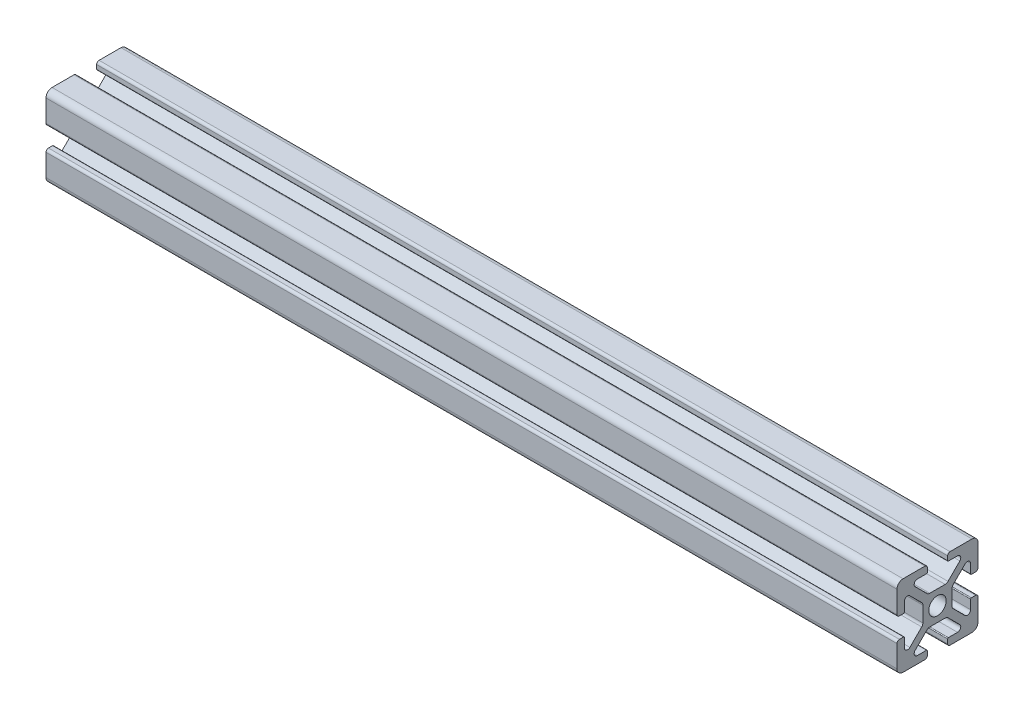
SolidWorks part; units mm, degrees
ref_plane "Front Plane" through (0, 0, 0) normal (0, 0, 1) x (1, 0, 0)
ref_plane "Top Plane" through (0, 0, 0) normal (0, 1, 0) x (1, 0, 0)
ref_plane "Right Plane" through (0, 0, 0) normal (1, 0, 0) x (0, 0, -1)
sketch "Sketch1" plane through (0, 0, 0) normal (1, 0, 0) x (0, 0, -1)
  line L0 (0, -10) -> (0, 10) construction
  line L1 (10, -10) -> (-10, -10)
  line L2 (10, -10) -> (10, 10)
  line L3 (10, 10) -> (0, 10)
  line L4 (-10, -10) -> (-10, 10)
  line L5 (10, -10) -> (-10, 10) construction
  line L6 (10, 10) -> (-10, -10) construction
  line L7 (10, 0) -> (-10, 0) construction
  line L8 (-2.5, 9.4) -> (-2.5, 8.3731)
  line L9 (-2.7, 8.1731) -> (-4.95, 8.1731)
  line L10 (-5.5157, 6.8075) -> (-2.6011, 3.8929)
  line L11 (-1.894, 3.6) -> (0, 3.6)
  line L12 (-5.3502, 4.0584) -> (-4.0584, 5.3502) construction
  line L13 (-3.825, 8.1731) -> (-3.825, 10) construction
  line L14 (-3.1, 10) -> (-10, 10)
  line L15 (-5.75, 7.3731) -> (5.75, 7.3731) construction
  circle A0 centre (0, 0) radius 2.15
  arc A1 (-4.95, 8.1731) -> (-5.5157, 6.8075) centre (-4.95, 7.3731) ccw
  arc A2 (-2.6011, 3.8929) -> (-1.894, 3.6) centre (-1.894, 4.6) ccw
  arc A3 (-2.5, 8.3731) -> (-2.7, 8.1731) centre (-2.7, 8.3731) cw
  arc A4 (-2.5, 9.4) -> (-3.1, 10) centre (-3.1, 9.4) ccw
  point P0 (0, 0)
  point P9 (0, 0)
  point P12 (0, 0)
  point P22 (-4.7043, 4.7043)
  point P32 (-2.5, 10)
  point P33 (-2.5, 8.8866)
  point P35 (-4.0584, 5.3502)
  point P37 (0, 7.3731)
  dimension "Center Hole Diameter" = 4.3
  dimension "D4" = 1
  dimension "D5" = 0.2
  dimension "D6" = 0.6
  dimension "D3" = 0.8
  dimension "Rail Height" = 20
  dimension "D7" = 6.4
  dimension "T Slot Width" = 5
  dimension "D10" = 10
  dimension "Rail Width" = 20
  dimension "D2" = 11.5
sketch "Sketch2" plane through (0, 0, 0) normal (0, 0, 1) x (1, 0, 0)
  line L0 (-132.4, 10) -> (-132.4, -10) construction
  line L1 (152.4, -10) -> (-152.4, -10) construction
  line L2 (152.4, -10) -> (152.4, 10) construction
  line L3 (152.4, 10) -> (-152.4, 10) construction
  line L4 (-152.4, -10) -> (-152.4, 10) construction
  line L5 (152.4, -10) -> (-152.4, 10) construction
  line L6 (152.4, 10) -> (-152.4, -10) construction
  line L7 (132.4, 10) -> (132.4, -10) construction
  point P0 (0, 0)
  point P12 (132.4, 0)
  dimension "Length" = 304.8
  dimension "D1" = 20
  dimension "D2" = 20
sketch "Sketch3" plane through (0, 0, 0) normal (1, 0, 0) x (0, 0, -1)
  line L0 (-5.5157, 6.8075) -> (-2.6011, 3.8929) construction
  line L5 (-3.1, 10) -> (-10, 10) construction
  line L6 (-2.5, 9.4) -> (-2.5, 8.3731) construction
  line L7 (-2.7, 8.1731) -> (-4.95, 8.1731) construction
  line L8 (-1.894, 3.6) -> (0, 3.6) construction
  line L9 (-5.5157, 6.8075) -> (-2.6011, 3.8929)
  line L10 (-10, 10) -> (0, 0) construction
  line L12 (-3.6, 1.894) -> (-3.6, 0)
  line L13 (-8.1731, 2.7) -> (-8.1731, 4.95)
  line L14 (-3.1, 10) -> (-8.5, 10)
  line L15 (-2.5, 9.4) -> (-2.5, 8.3731)
  line L16 (-2.7, 8.1731) -> (-4.95, 8.1731)
  line L17 (-1.894, 3.6) -> (0, 3.6)
  line L18 (-9.4, 2.5) -> (-8.3731, 2.5)
  line L19 (-10, 3.1) -> (-10, 8.5)
  line L20 (-6.8075, 5.5157) -> (-3.8929, 2.6011)
  line L21 (-3.6, 0) -> (-2.15, 0)
  line L22 (0, 3.6) -> (0, 2.15)
  arc A0 (-2.5, 9.4) -> (-3.1, 10) centre (-3.1, 9.4) ccw construction
  arc A1 (-2.7, 8.1731) -> (-2.5, 8.3731) centre (-2.7, 8.3731) ccw construction
  arc A2 (-4.95, 8.1731) -> (-5.5157, 6.8075) centre (-4.95, 7.3731) ccw construction
  arc A3 (-2.6011, 3.8929) -> (-1.894, 3.6) centre (-1.894, 4.6) ccw construction
  arc A4 (-2.5, 9.4) -> (-3.1, 10) centre (-3.1, 9.4) ccw
  arc A5 (-2.7, 8.1731) -> (-2.5, 8.3731) centre (-2.7, 8.3731) ccw
  arc A6 (-4.95, 8.1731) -> (-5.5157, 6.8075) centre (-4.95, 7.3731) ccw
  arc A7 (-2.6011, 3.8929) -> (-1.894, 3.6) centre (-1.894, 4.6) ccw
  arc A8 (-3.8929, 2.6011) -> (-3.6, 1.894) centre (-4.6, 1.894) cw
  arc A9 (-8.1731, 4.95) -> (-6.8075, 5.5157) centre (-7.3731, 4.95) cw
  arc A10 (-8.1731, 2.7) -> (-8.3731, 2.5) centre (-8.3731, 2.7) cw
  arc A11 (-9.4, 2.5) -> (-10, 3.1) centre (-9.4, 3.1) cw
  circle A12 centre (0, 0) radius 2.15 construction
  arc A13 (0, 2.15) -> (-2.15, 0) centre (0, 0) ccw
  arc A14 (-10, 8.5) -> (-8.5, 10) centre (-8.5, 8.5) cw
  dimension "D1" = 1.5
extrude "Boss-Extrude1" add sketch "Sketch3" against normal up to vertex (152.4 mm away) and the other way up to vertex (152.4 mm away) up to point (-152.4, 10, 0) other way up to point (152.4, 10, 0)
mirror "Mirror1" about plane through (0, 0, 0) normal (0, 1, 0) of bodies 104
mirror "Mirror2" about plane through (0, 0, 0) normal (0, 0, 1) of bodies 105
sketch "Sketch4" plane through (152.4, 0, 0) normal (1, 0, 0) x (0, 0, -1)
  line L36 (1.894, 3.6) -> (-1.894, 3.6)
  line L37 (-2.6011, 3.8929) -> (-5.5157, 6.8075)
  line L38 (-4.95, 8.1731) -> (-2.7, 8.1731)
  line L39 (-2.5, 8.3731) -> (-2.5, 9.4)
  line L40 (-3.1, 10) -> (-8.5, 10)
  line L41 (-10, 8.5) -> (-10, 3.1)
  line L42 (-9.4, 2.5) -> (-8.3731, 2.5)
  line L43 (-8.1731, 2.7) -> (-8.1731, 4.95)
  line L44 (-6.8075, 5.5157) -> (-3.8929, 2.6011)
  line L45 (-3.6, 1.894) -> (-3.6, -1.894)
  line L46 (-3.8929, -2.6011) -> (-6.8075, -5.5157)
  line L47 (-8.1731, -4.95) -> (-8.1731, -2.7)
  line L48 (-8.3731, -2.5) -> (-9.4, -2.5)
  line L49 (-10, -3.1) -> (-10, -8.5)
  line L50 (-8.5, -10) -> (-3.1, -10)
  line L51 (-2.5, -9.4) -> (-2.5, -8.3731)
  line L52 (-2.7, -8.1731) -> (-4.95, -8.1731)
  line L53 (-5.5157, -6.8075) -> (-2.6011, -3.8929)
  line L54 (-1.894, -3.6) -> (1.894, -3.6)
  line L55 (2.6011, -3.8929) -> (5.5157, -6.8075)
  line L56 (4.95, -8.1731) -> (2.7, -8.1731)
  line L57 (2.5, -8.3731) -> (2.5, -9.4)
  line L58 (3.1, -10) -> (8.5, -10)
  line L59 (10, -8.5) -> (10, -3.1)
  line L60 (9.4, -2.5) -> (8.3731, -2.5)
  line L61 (8.1731, -2.7) -> (8.1731, -4.95)
  line L62 (6.8075, -5.5157) -> (3.8929, -2.6011)
  line L63 (3.6, -1.894) -> (3.6, 1.894)
  line L64 (3.8929, 2.6011) -> (6.8075, 5.5157)
  line L65 (8.1731, 4.95) -> (8.1731, 2.7)
  line L66 (8.3731, 2.5) -> (9.4, 2.5)
  line L67 (10, 3.1) -> (10, 8.5)
  line L68 (8.5, 10) -> (3.1, 10)
  line L69 (2.5, 9.4) -> (2.5, 8.3731)
  line L70 (2.7, 8.1731) -> (4.95, 8.1731)
  line L71 (5.5157, 6.8075) -> (2.6011, 3.8929)
  line L72 (1.894, 3.6) -> (-1.894, 3.6)
  line L73 (-2.6011, 3.8929) -> (-5.5157, 6.8075)
  line L74 (-4.95, 8.1731) -> (-2.7, 8.1731)
  line L75 (-2.5, 8.3731) -> (-2.5, 9.4)
  line L76 (-3.1, 10) -> (-8.5, 10)
  line L77 (-10, 8.5) -> (-10, 3.1)
  line L78 (-9.4, 2.5) -> (-8.3731, 2.5)
  line L79 (-8.1731, 2.7) -> (-8.1731, 4.95)
  line L80 (-6.8075, 5.5157) -> (-3.8929, 2.6011)
  line L81 (-3.6, 1.894) -> (-3.6, -1.894)
  line L82 (-3.8929, -2.6011) -> (-6.8075, -5.5157)
  line L83 (-8.1731, -4.95) -> (-8.1731, -2.7)
  line L84 (-8.3731, -2.5) -> (-9.4, -2.5)
  line L85 (-10, -3.1) -> (-10, -8.5)
  line L86 (-8.5, -10) -> (-3.1, -10)
  line L87 (-2.5, -9.4) -> (-2.5, -8.3731)
  line L88 (-2.7, -8.1731) -> (-4.95, -8.1731)
  line L89 (-5.5157, -6.8075) -> (-2.6011, -3.8929)
  line L90 (-1.894, -3.6) -> (1.894, -3.6)
  line L91 (2.6011, -3.8929) -> (5.5157, -6.8075)
  line L92 (4.95, -8.1731) -> (2.7, -8.1731)
  line L93 (2.5, -8.3731) -> (2.5, -9.4)
  line L94 (3.1, -10) -> (8.5, -10)
  line L95 (10, -8.5) -> (10, -3.1)
  line L96 (9.4, -2.5) -> (8.3731, -2.5)
  line L97 (8.1731, -2.7) -> (8.1731, -4.95)
  line L98 (6.8075, -5.5157) -> (3.8929, -2.6011)
  line L99 (3.6, -1.894) -> (3.6, 1.894)
  line L100 (3.8929, 2.6011) -> (6.8075, 5.5157)
  line L101 (8.1731, 4.95) -> (8.1731, 2.7)
  line L102 (8.3731, 2.5) -> (9.4, 2.5)
  line L103 (10, 3.1) -> (10, 8.5)
  line L104 (8.5, 10) -> (3.1, 10)
  line L105 (2.5, 9.4) -> (2.5, 8.3731)
  line L106 (2.7, 8.1731) -> (4.95, 8.1731)
  line L107 (5.5157, 6.8075) -> (2.6011, 3.8929)
  circle A0 centre (0, 0) radius 2.15 construction
  circle A1 centre (0, 0) radius 2.15
  arc A36 (1.894, 3.6) -> (2.6011, 3.8929) centre (1.894, 4.6) ccw
  arc A37 (-2.6011, 3.8929) -> (-1.894, 3.6) centre (-1.894, 4.6) ccw
  arc A38 (-4.95, 8.1731) -> (-5.5157, 6.8075) centre (-4.95, 7.3731) ccw
  arc A39 (-2.7, 8.1731) -> (-2.5, 8.3731) centre (-2.7, 8.3731) ccw
  arc A40 (-2.5, 9.4) -> (-3.1, 10) centre (-3.1, 9.4) ccw
  arc A41 (-8.5, 10) -> (-10, 8.5) centre (-8.5, 8.5) ccw
  arc A42 (-10, 3.1) -> (-9.4, 2.5) centre (-9.4, 3.1) ccw
  arc A43 (-8.3731, 2.5) -> (-8.1731, 2.7) centre (-8.3731, 2.7) ccw
  arc A44 (-6.8075, 5.5157) -> (-8.1731, 4.95) centre (-7.3731, 4.95) ccw
  arc A45 (-3.6, 1.894) -> (-3.8929, 2.6011) centre (-4.6, 1.894) ccw
  arc A46 (-3.8929, -2.6011) -> (-3.6, -1.894) centre (-4.6, -1.894) ccw
  arc A47 (-8.1731, -4.95) -> (-6.8075, -5.5157) centre (-7.3731, -4.95) ccw
  arc A48 (-8.1731, -2.7) -> (-8.3731, -2.5) centre (-8.3731, -2.7) ccw
  arc A49 (-9.4, -2.5) -> (-10, -3.1) centre (-9.4, -3.1) ccw
  arc A50 (-10, -8.5) -> (-8.5, -10) centre (-8.5, -8.5) ccw
  arc A51 (-3.1, -10) -> (-2.5, -9.4) centre (-3.1, -9.4) ccw
  arc A52 (-2.5, -8.3731) -> (-2.7, -8.1731) centre (-2.7, -8.3731) ccw
  arc A53 (-5.5157, -6.8075) -> (-4.95, -8.1731) centre (-4.95, -7.3731) ccw
  arc A54 (-1.894, -3.6) -> (-2.6011, -3.8929) centre (-1.894, -4.6) ccw
  arc A55 (2.6011, -3.8929) -> (1.894, -3.6) centre (1.894, -4.6) ccw
  arc A56 (4.95, -8.1731) -> (5.5157, -6.8075) centre (4.95, -7.3731) ccw
  arc A57 (2.7, -8.1731) -> (2.5, -8.3731) centre (2.7, -8.3731) ccw
  arc A58 (2.5, -9.4) -> (3.1, -10) centre (3.1, -9.4) ccw
  arc A59 (8.5, -10) -> (10, -8.5) centre (8.5, -8.5) ccw
  arc A60 (10, -3.1) -> (9.4, -2.5) centre (9.4, -3.1) ccw
  arc A61 (8.3731, -2.5) -> (8.1731, -2.7) centre (8.3731, -2.7) ccw
  arc A62 (6.8075, -5.5157) -> (8.1731, -4.95) centre (7.3731, -4.95) ccw
  arc A63 (3.6, -1.894) -> (3.8929, -2.6011) centre (4.6, -1.894) ccw
  arc A64 (3.8929, 2.6011) -> (3.6, 1.894) centre (4.6, 1.894) ccw
  arc A65 (8.1731, 4.95) -> (6.8075, 5.5157) centre (7.3731, 4.95) ccw
  arc A66 (8.1731, 2.7) -> (8.3731, 2.5) centre (8.3731, 2.7) ccw
  arc A67 (9.4, 2.5) -> (10, 3.1) centre (9.4, 3.1) ccw
  arc A68 (10, 8.5) -> (8.5, 10) centre (8.5, 8.5) ccw
  arc A69 (3.1, 10) -> (2.5, 9.4) centre (3.1, 9.4) ccw
  arc A70 (2.5, 8.3731) -> (2.7, 8.1731) centre (2.7, 8.3731) ccw
  arc A71 (5.5157, 6.8075) -> (4.95, 8.1731) centre (4.95, 7.3731) ccw
  arc A72 (1.894, 3.6) -> (2.6011, 3.8929) centre (1.894, 4.6) ccw
  arc A73 (-2.6011, 3.8929) -> (-1.894, 3.6) centre (-1.894, 4.6) ccw
  arc A74 (-4.95, 8.1731) -> (-5.5157, 6.8075) centre (-4.95, 7.3731) ccw
  arc A75 (-2.7, 8.1731) -> (-2.5, 8.3731) centre (-2.7, 8.3731) ccw
  arc A76 (-2.5, 9.4) -> (-3.1, 10) centre (-3.1, 9.4) ccw
  arc A77 (-8.5, 10) -> (-10, 8.5) centre (-8.5, 8.5) ccw
  arc A78 (-10, 3.1) -> (-9.4, 2.5) centre (-9.4, 3.1) ccw
  arc A79 (-8.3731, 2.5) -> (-8.1731, 2.7) centre (-8.3731, 2.7) ccw
  arc A80 (-6.8075, 5.5157) -> (-8.1731, 4.95) centre (-7.3731, 4.95) ccw
  arc A81 (-3.6, 1.894) -> (-3.8929, 2.6011) centre (-4.6, 1.894) ccw
  arc A82 (-3.8929, -2.6011) -> (-3.6, -1.894) centre (-4.6, -1.894) ccw
  arc A83 (-8.1731, -4.95) -> (-6.8075, -5.5157) centre (-7.3731, -4.95) ccw
  arc A84 (-8.1731, -2.7) -> (-8.3731, -2.5) centre (-8.3731, -2.7) ccw
  arc A85 (-9.4, -2.5) -> (-10, -3.1) centre (-9.4, -3.1) ccw
  arc A86 (-10, -8.5) -> (-8.5, -10) centre (-8.5, -8.5) ccw
  arc A87 (-3.1, -10) -> (-2.5, -9.4) centre (-3.1, -9.4) ccw
  arc A88 (-2.5, -8.3731) -> (-2.7, -8.1731) centre (-2.7, -8.3731) ccw
  arc A89 (-5.5157, -6.8075) -> (-4.95, -8.1731) centre (-4.95, -7.3731) ccw
  arc A90 (-1.894, -3.6) -> (-2.6011, -3.8929) centre (-1.894, -4.6) ccw
  arc A91 (2.6011, -3.8929) -> (1.894, -3.6) centre (1.894, -4.6) ccw
  arc A92 (4.95, -8.1731) -> (5.5157, -6.8075) centre (4.95, -7.3731) ccw
  arc A93 (2.7, -8.1731) -> (2.5, -8.3731) centre (2.7, -8.3731) ccw
  arc A94 (2.5, -9.4) -> (3.1, -10) centre (3.1, -9.4) ccw
  arc A95 (8.5, -10) -> (10, -8.5) centre (8.5, -8.5) ccw
  arc A96 (10, -3.1) -> (9.4, -2.5) centre (9.4, -3.1) ccw
  arc A97 (8.3731, -2.5) -> (8.1731, -2.7) centre (8.3731, -2.7) ccw
  arc A98 (6.8075, -5.5157) -> (8.1731, -4.95) centre (7.3731, -4.95) ccw
  arc A99 (3.6, -1.894) -> (3.8929, -2.6011) centre (4.6, -1.894) ccw
  arc A100 (3.8929, 2.6011) -> (3.6, 1.894) centre (4.6, 1.894) ccw
  arc A101 (8.1731, 4.95) -> (6.8075, 5.5157) centre (7.3731, 4.95) ccw
  arc A102 (8.1731, 2.7) -> (8.3731, 2.5) centre (8.3731, 2.7) ccw
  arc A103 (9.4, 2.5) -> (10, 3.1) centre (9.4, 3.1) ccw
  arc A104 (10, 8.5) -> (8.5, 10) centre (8.5, 8.5) ccw
  arc A105 (3.1, 10) -> (2.5, 9.4) centre (3.1, 9.4) ccw
  arc A106 (2.5, 8.3731) -> (2.7, 8.1731) centre (2.7, 8.3731) ccw
  arc A107 (5.5157, 6.8075) -> (4.95, 8.1731) centre (4.95, 7.3731) ccw
  dimension "D1" = 0
extrude "Cut-Extrude1" cut sketch "Sketch4" against normal offset from surface (94.8 mm away) 210 up to face at (-152.4, 0, 0)
equation "\"D10@Sketch1\" = \"Rail Height@Sketch1\" / 2"
equation "\"D2@Sketch2\"=\"D1@Sketch2\""
